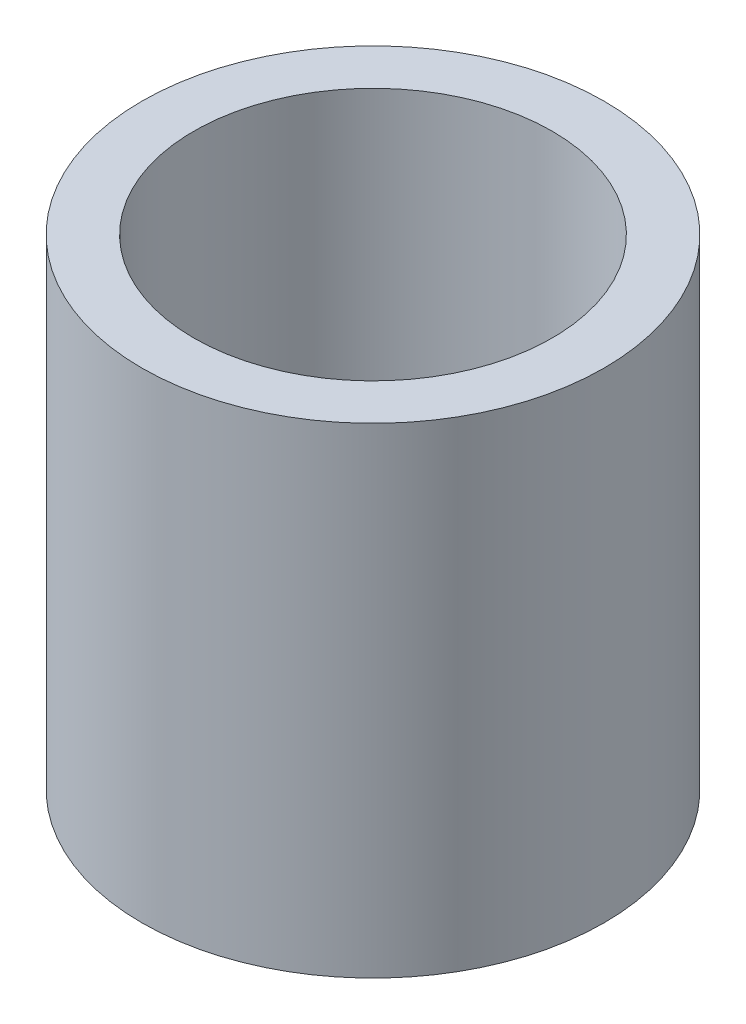
SolidWorks part; units mm, degrees
material "PTFE (general)"
ref_plane "Front Plane" through (0, 0, 0) normal (0, 0, 1) x (1, 0, 0)
ref_plane "Top Plane" through (0, 0, 0) normal (0, 1, 0) x (1, 0, 0)
ref_plane "Right Plane" through (0, 0, 0) normal (1, 0, 0) x (0, 0, -1)
sketch "Sketch1" plane through (0, 0, 0) normal (0, 1, 0) x (1, 0, 0)
  circle A0 centre (0, 0) radius 6.9
  circle A1 centre (0, 0) radius 8.9
  dimension "D1" = 17.8
  dimension "D2" = 13.8
extrude "Boss-Extrude1" add sketch "Sketch1" along normal blind 18.5
